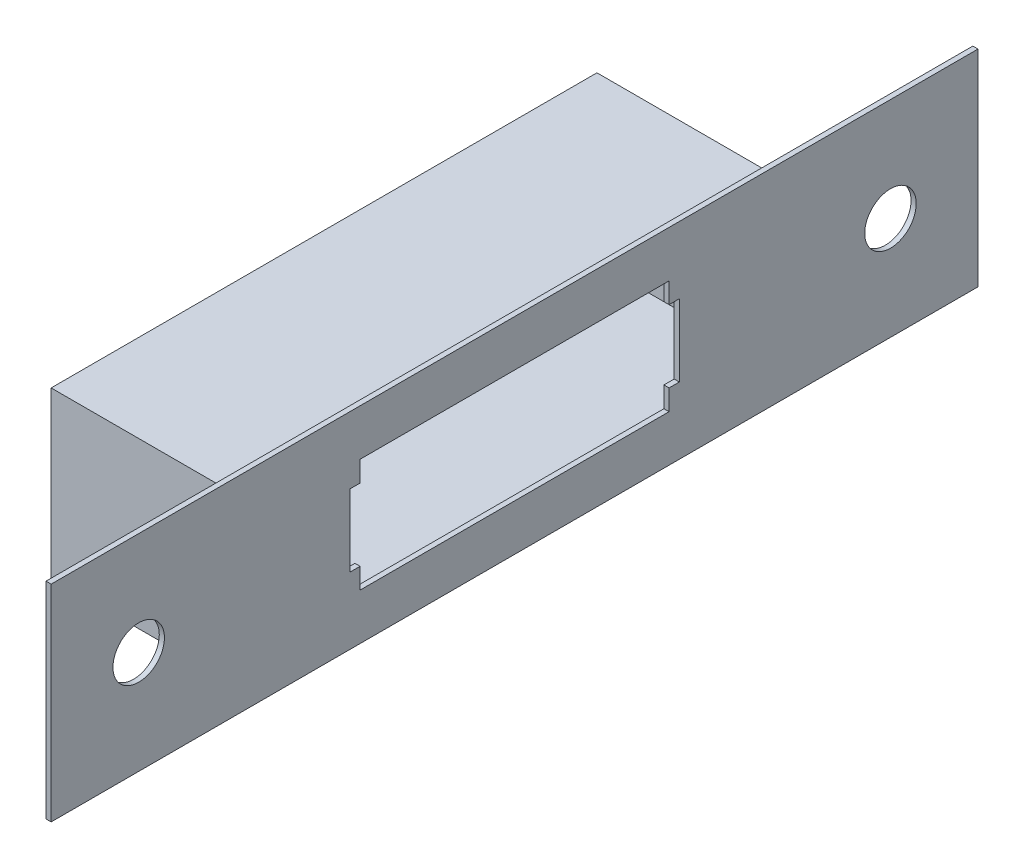
SolidWorks part; units mm, degrees
material "Stainless Steel (ferritic)"
ref_plane "Front Plane" through (0, 0, 0) normal (0, 0, 1) x (1, 0, 0)
ref_plane "Top Plane" through (0, 0, 0) normal (0, 1, 0) x (1, 0, 0)
ref_plane "Right Plane" through (0, 0, 0) normal (1, 0, 0) x (0, 0, -1)
sketch "Sketch1" plane through (0, 0, 0) normal (1, 0, 0) x (0, 0, -1)
  line L1 (-26.5, -8) -> (26.5, -8)
  line L2 (-26.5, -8) -> (-26.5, 8)
  line L3 (-26.5, 8) -> (26.5, 8)
  line L4 (26.5, -8) -> (26.5, 8)
  line L5 (-26.5, -8) -> (26.5, 8) construction
  line L6 (-26.5, 8) -> (26.5, -8) construction
  point P0 (0, 0)
  dimension "D1" = 53
  dimension "D2" = 16
extrude "Boss-Extrude1" add sketch "Sketch1" along normal blind 18
shell "Shell1" thickness 0.5
sketch "Sketch2" plane through (18, 0, 0) normal (1, 0, 0) x (0, 0, -1)
  line L0 (-36.5, 0) -> (36.5, 0) construction
  line L1 (-45, -10) -> (45, -10)
  line L2 (-45, -10) -> (-45, 10)
  line L3 (-45, 10) -> (45, 10)
  line L4 (45, -10) -> (45, 10)
  line L5 (-45, -10) -> (45, 10) construction
  line L6 (-45, 10) -> (45, -10) construction
  line L7 (-16, 3.5) -> (-15, 3.5)
  line L8 (-15, -5.5) -> (15, -5.5)
  line L9 (-15, -5.5) -> (-15, 5.5) construction
  line L10 (-15, 5.5) -> (15, 5.5)
  line L11 (15, -5.5) -> (15, 5.5) construction
  line L12 (-15, -5.5) -> (15, 5.5) construction
  line L13 (-15, 5.5) -> (15, -5.5) construction
  line L14 (-16, -3.5) -> (16, -3.5) construction
  line L15 (-16, -3.5) -> (-16, 3.5)
  line L16 (-16, 3.5) -> (16, 3.5) construction
  line L17 (16, -3.5) -> (16, 3.5)
  line L18 (-16, -3.5) -> (16, 3.5) construction
  line L19 (-16, 3.5) -> (16, -3.5) construction
  line L20 (-16, -3.5) -> (-15, -3.5)
  line L21 (15, 3.5) -> (16, 3.5)
  line L22 (16, -3.5) -> (15, -3.5)
  line L23 (-15, 5.5) -> (-15, 3.5)
  line L24 (-15, -5.5) -> (-15, -3.5)
  line L25 (15, -3.5) -> (15, -5.5)
  line L26 (15, 5.5) -> (15, 3.5)
  circle A0 centre (36.5, 0) radius 2.5
  circle A1 centre (-36.5, 0) radius 2.5
  point P0 (0, 0)
  point P10 (0, 0)
  point P15 (0, 0)
  dimension "D6" = 5
  dimension "D1" = 90
  dimension "D2" = 20
  dimension "D3" = 73
  dimension "D4" = 30
  dimension "D5" = 11
  dimension "D7" = 7
  dimension "D8" = 32
extrude "Boss-Extrude2" add sketch "Sketch2" along normal blind 0.5
